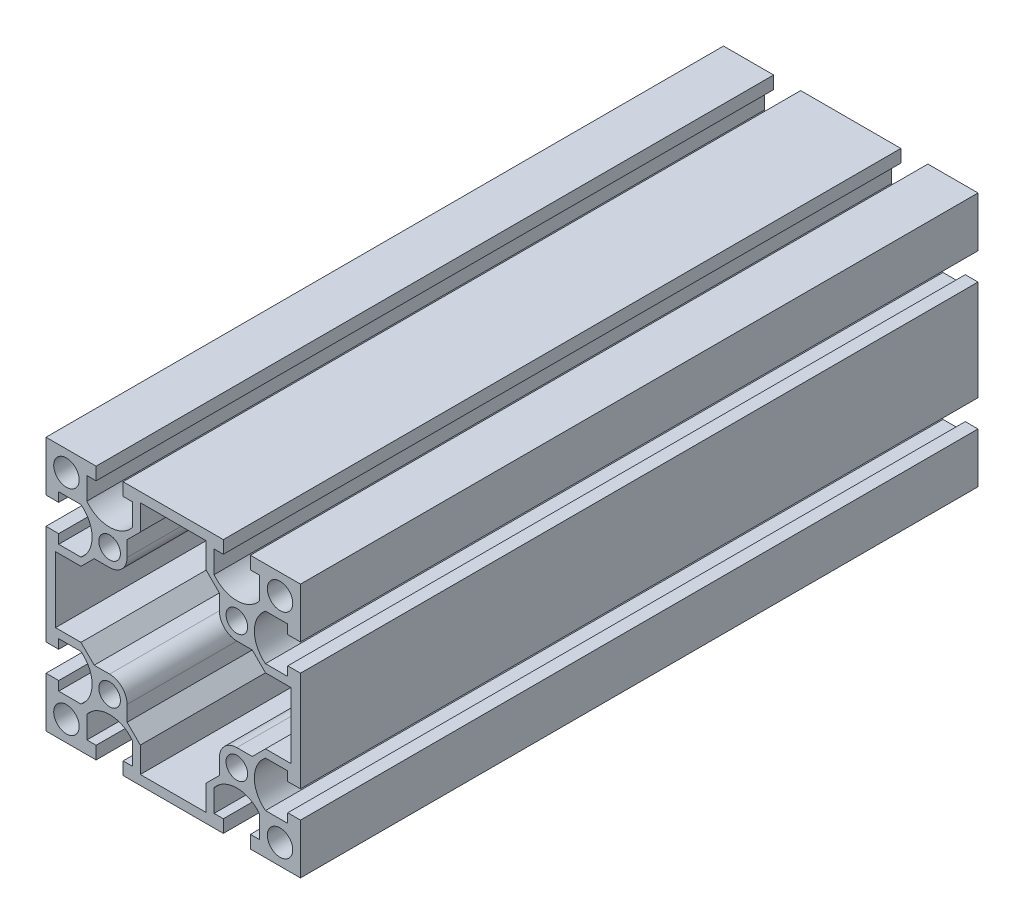
SolidWorks part; units mm, degrees
ref_plane "前视基准面" through (0, 0, 0) normal (0, 0, 1) x (1, 0, 0)
ref_plane "上视基准面" through (0, 0, 0) normal (0, 1, 0) x (1, 0, 0)
ref_plane "右视基准面" through (0, 0, 0) normal (1, 0, 0) x (0, 0, -1)
other "Configuration Table"
sketch "草图1" plane through (0, 0, 0) normal (0, 0, 1) x (1, 0, 0)
  line L0 (0, 0) -> (0, 50.1573) construction
  line L1 (0, 0) -> (-73.5163, 0) construction
  line L2 (0, 0) -> (-54.4301, 54.4301) construction
  line L3 (-40, 40) -> (-24.25, 40)
  line L4 (-40, 40) -> (-40, 24.25) construction
  line L7 (-24.25, 40) -> (-24.25, 36)
  line L8 (-24.25, 36) -> (-27.15, 36)
  line L9 (-27.15, 36) -> (-27.15, 29)
  line L10 (-15.75, 40) -> (-15.75, 36)
  line L11 (-15.75, 36) -> (-12.85, 36)
  line L12 (-12.85, 36) -> (-12.85, 29)
  line L13 (10.35, 37) -> (-10.35, 37)
  line L14 (-10.35, 37) -> (-10.35, 29)
  line L15 (-20, 46.3565) -> (-20, 13.3226) construction
  line L16 (-22.6887, 25.5) -> (-15.1183, 25.5) construction
  line L17 (-10.35, 29) -> (-14.5, 24.85)
  line L18 (-14.5, 24.85) -> (-14.5, 20)
  line L19 (-33.575, 44.626) -> (-33.575, 38.1973) construction
  line L20 (-44.626, 33.575) -> (-38.1973, 33.575) construction
  line L21 (-25.5, 22.6887) -> (-25.5, 5.6618) construction
  line L22 (-43.4182, 20) -> (-13.3226, 20) construction
  line L23 (-24.85, 14.5) -> (-20, 14.5)
  line L24 (-29, 10.35) -> (-24.85, 14.5)
  line L25 (-37, 10.35) -> (-29, 10.35)
  line L26 (-37, -10.35) -> (-37, 10.35)
  line L27 (-36, 12.85) -> (-29, 12.85)
  line L28 (-36, 15.75) -> (-36, 12.85)
  line L29 (-40.0003, 15.75) -> (-36, 15.75)
  line L30 (-36, 27.15) -> (-29, 27.15)
  line L31 (-36, 24.25) -> (-36, 27.15)
  line L32 (-40, 24.25) -> (-36, 24.25)
  line L33 (-40, 40) -> (-40, 24.25)
  line L34 (46.3565, 20) -> (13.3226, 20) construction
  line L35 (25.5, 22.6887) -> (25.5, 5.6618) construction
  line L36 (44.626, 33.575) -> (38.1973, 33.575) construction
  line L37 (33.575, 44.626) -> (33.575, 38.1973) construction
  line L38 (22.6887, 25.5) -> (15.1183, 25.5) construction
  line L39 (20, 46.3565) -> (20, 13.3226) construction
  line L40 (40, 40) -> (40, 24.25) construction
  line L41 (40, 40) -> (40, 24.25)
  line L42 (40, 24.25) -> (36, 24.25)
  line L43 (36, 24.25) -> (36, 27.15)
  line L44 (36, 27.15) -> (29, 27.15)
  line L45 (40.0003, 15.75) -> (36, 15.75)
  line L46 (36, 15.75) -> (36, 12.85)
  line L47 (36, 12.85) -> (29, 12.85)
  line L48 (37, -10.35) -> (37, 10.35)
  line L49 (37, 10.35) -> (29, 10.35)
  line L50 (29, 10.35) -> (24.85, 14.5)
  line L51 (24.85, 14.5) -> (20, 14.5)
  line L52 (14.5, 24.85) -> (14.5, 20)
  line L53 (10.35, 29) -> (14.5, 24.85)
  line L54 (10.35, 37) -> (10.35, 29)
  line L55 (12.85, 36) -> (12.85, 29)
  line L56 (15.75, 36) -> (12.85, 36)
  line L57 (15.75, 40) -> (15.75, 36)
  line L58 (27.15, 36) -> (27.15, 29)
  line L59 (24.25, 36) -> (27.15, 36)
  line L60 (24.25, 40) -> (24.25, 36)
  line L61 (22.6887, -25.5) -> (15.1183, -25.5) construction
  line L62 (44.626, -33.575) -> (38.1973, -33.575) construction
  line L63 (25.5, -22.6887) -> (25.5, -5.6618) construction
  line L64 (46.3565, -20) -> (13.3226, -20) construction
  line L65 (-46.3565, -20) -> (-13.3226, -20) construction
  line L66 (-25.5, -22.6887) -> (-25.5, -5.6618) construction
  line L67 (-44.626, -33.575) -> (-38.1973, -33.575) construction
  line L68 (-22.6887, -25.5) -> (-15.1183, -25.5) construction
  line L69 (24.25, -40) -> (24.25, -36)
  line L70 (24.25, -36) -> (27.15, -36)
  line L71 (27.15, -36) -> (27.15, -29)
  line L72 (15.75, -40) -> (15.75, -36)
  line L73 (15.75, -36) -> (12.85, -36)
  line L74 (12.85, -36) -> (12.85, -29)
  line L75 (10.35, -37) -> (10.35, -29)
  line L76 (10.35, -29) -> (14.5, -24.85)
  line L77 (14.5, -24.85) -> (14.5, -20)
  line L78 (24.85, -14.5) -> (20, -14.5)
  line L79 (29, -10.35) -> (24.85, -14.5)
  line L80 (37, -10.35) -> (29, -10.35)
  line L81 (36, -12.85) -> (29, -12.85)
  line L82 (36, -15.75) -> (36, -12.85)
  line L83 (40.0003, -15.75) -> (36, -15.75)
  line L84 (36, -27.15) -> (29, -27.15)
  line L85 (36, -24.25) -> (36, -27.15)
  line L86 (40, -24.25) -> (36, -24.25)
  line L87 (-40, -24.25) -> (-36, -24.25)
  line L88 (-36, -24.25) -> (-36, -27.15)
  line L89 (-36, -27.15) -> (-29, -27.15)
  line L90 (-40.0003, -15.75) -> (-36, -15.75)
  line L91 (-36, -15.75) -> (-36, -12.85)
  line L92 (-36, -12.85) -> (-29, -12.85)
  line L93 (-37, -10.35) -> (-29, -10.35)
  line L94 (-29, -10.35) -> (-24.85, -14.5)
  line L95 (-24.85, -14.5) -> (-20, -14.5)
  line L96 (-14.5, -24.85) -> (-14.5, -20)
  line L97 (-10.35, -29) -> (-14.5, -24.85)
  line L98 (-10.35, -37) -> (-10.35, -29)
  line L99 (10.35, -37) -> (-10.35, -37)
  line L100 (-12.85, -36) -> (-12.85, -29)
  line L101 (-15.75, -36) -> (-12.85, -36)
  line L102 (-15.75, -40) -> (-15.75, -36)
  line L103 (-27.15, -36) -> (-27.15, -29)
  line L104 (-24.25, -36) -> (-27.15, -36)
  line L105 (-24.25, -40) -> (-24.25, -36)
  line L106 (-40, -40) -> (-24.25, -40)
  line L107 (40, -24.25) -> (40, -40) construction
  line L108 (40, -24.25) -> (40, -40)
  line L109 (24.25, -40) -> (40, -40)
  line L110 (-15.75, -40) -> (15.75, -40)
  line L111 (-40, 15.75) -> (-40, -15.75) construction
  line L112 (-40, 15.75) -> (-40, -15.75)
  line L113 (24.25, 40) -> (40, 40)
  line L114 (40, 15.75) -> (40, -15.75) construction
  line L115 (40, 15.75) -> (40, -15.75)
  line L116 (-40, -24.25) -> (-40, -40) construction
  line L117 (-40, -24.25) -> (-40, -40)
  line L118 (-15.75, 40) -> (15.75, 40)
  arc A0 (-27.15, 29) -> (-12.85, 29) centre (-20, 34.5532) ccw
  circle A1 centre (-20, 20) radius 3.4
  arc A2 (-20, 14.5) -> (-14.5, 20) centre (-20, 20) ccw
  circle A3 centre (-33.575, 33.575) radius 4
  arc A4 (-29, 27.15) -> (-29, 12.85) centre (-34.5532, 20) cw
  arc A5 (29, 27.15) -> (29, 12.85) centre (34.5532, 20) ccw
  circle A6 centre (33.575, 33.575) radius 4
  arc A7 (20, 14.5) -> (14.5, 20) centre (20, 20) cw
  circle A8 centre (20, 20) radius 3.4
  arc A9 (27.15, 29) -> (12.85, 29) centre (20, 34.5532) cw
  arc A10 (27.15, -29) -> (12.85, -29) centre (20, -34.5532) ccw
  circle A11 centre (20, -20) radius 3.4
  arc A12 (20, -14.5) -> (14.5, -20) centre (20, -20) ccw
  circle A13 centre (33.575, -33.575) radius 4
  arc A14 (29, -27.15) -> (29, -12.85) centre (34.5532, -20) cw
  arc A15 (-29, -27.15) -> (-29, -12.85) centre (-34.5532, -20) ccw
  circle A16 centre (-33.575, -33.575) radius 4
  arc A17 (-20, -14.5) -> (-14.5, -20) centre (-20, -20) cw
  circle A18 centre (-20, -20) radius 3.4
  arc A19 (-27.15, -29) -> (-12.85, -29) centre (-20, -34.5532) cw
  point P66 (-40, 0)
  point P92 (0, 37)
  point P98 (0, 40)
  point P152 (37, 0)
  point P158 (40, 0)
  point P165 (-37, 0)
  point P176 (0, -40)
  point P177 (0, -37)
  dimension "D12" = 6.8
  dimension "D13" = 11
  dimension "D15" = 8
  dimension "D18" = 80
  dimension "D1" = 40
  dimension "D2" = 40
  dimension "D3" = 45
  dimension "D4" = 20
  dimension "D5" = 8.5
  dimension "D6" = 4
  dimension "D7" = 3
  dimension "D8" = 11
  dimension "D9" = 14.3
  dimension "D10" = 14.5
  dimension "D11" = 2.5
  dimension "D14" = 45
  dimension "D16" = 3
  dimension "D17" = 45
  dimension "D19" = 80
extrude "凸台-拉伸1" add sketch "草图1" along normal mid plane 213 contours L103 A19 L100 L101 L102 L110 L72 L73 L74 A10 L71 L70 L69 L109 L108 L86 L85 L84 A14 L81 L82 L83 L115 L45 L46 L47 A5 L44 L43 L42 L41 L113 L60 L59 L58 A9 L55 L56 L57 L118 L10 L11 L12 A0 L9 L8 L7 L3 L33 L32 L31
